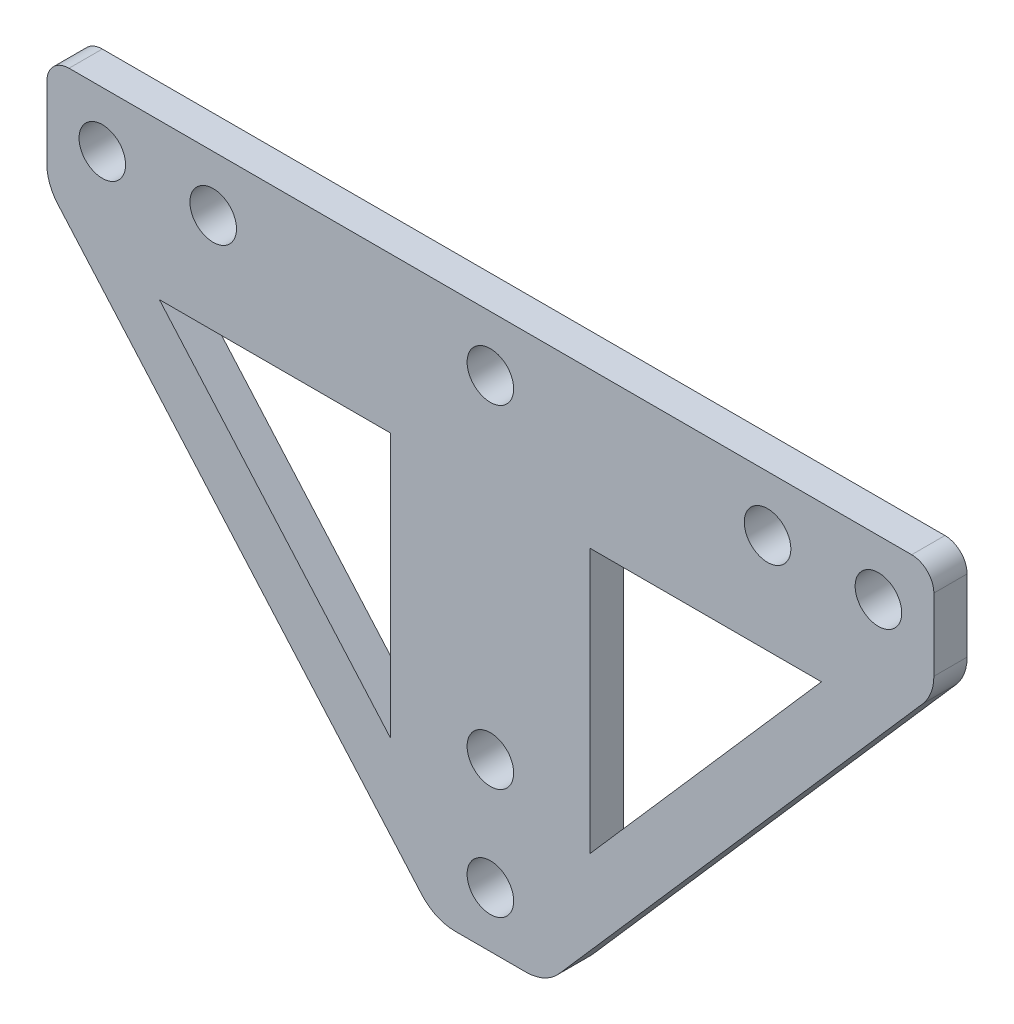
SolidWorks part; units mm, degrees
ref_plane "前视基准面" through (0, 0, 0) normal (0, 0, 1) x (1, 0, 0)
ref_plane "上视基准面" through (0, 0, 0) normal (0, 1, 0) x (1, 0, 0)
ref_plane "右视基准面" through (0, 0, 0) normal (1, 0, 0) x (0, 0, -1)
other "Configuration Table"
sketch "草图1" plane through (0, 0, 0) normal (0, 0, 1) x (1, 0, 0)
  line L0 (0, 0) -> (80, 0)
  line L1 (80, 0) -> (80, -10)
  line L2 (80, -10) -> (45, -50)
  line L3 (45, -50) -> (35, -50)
  line L4 (35, -50) -> (0, -10)
  line L5 (0, -10) -> (0, 0)
  line L6 (40, 0) -> (40, -50) construction
  point P9 (0, -10)
  point P10 (0, 0)
  dimension "D1" = 10
  dimension "D2" = 10
  dimension "D3" = 80
  dimension "D4" = 40
extrude "凸台-拉伸1" add sketch "草图1" along normal blind 3
sketch "草图2" plane through (0, 0, 3) normal (0, 0, 1) x (1, 0, 0)
  line L0 (0, -5) -> (80, -5) construction
  line L1 (0, 0) -> (0, -10) construction
  line L2 (80, -10) -> (80, 0) construction
  line L3 (40, -50) -> (40, 0) construction
  line L4 (35, -50) -> (45, -50) construction
  line L5 (80, 0) -> (0, 0) construction
  circle A0 centre (5, -5) radius 2.1
  circle A1 centre (15, -5) radius 2.1
  circle A2 centre (65, -5) radius 2.1
  circle A3 centre (75, -5) radius 2.1
  circle A4 centre (40, -45) radius 2.1
  circle A5 centre (40, -35) radius 2.1
  circle A6 centre (40, -5) radius 2.1
  dimension "D1" = 4.2
  dimension "D2" = 5
  dimension "D4" = 4.2
  dimension "D6" = 10
  dimension "D7" = 4.2
  dimension "D3" = 10
  dimension "D5" = 5
extrude "切除-拉伸1" cut sketch "草图2" against normal through all
sketch "草图3" plane through (0, 0, 3) normal (0, 0, 1) x (1, 0, 0)
  line L0 (10.1438, -14) -> (31, -14)
  line L1 (31, -14) -> (31, -37.8356)
  line L2 (31, -37.8356) -> (10.1438, -14)
  line L3 (40, 0) -> (40, -50) construction
  line L4 (80, 0) -> (0, 0) construction
  line L5 (35, -50) -> (45, -50) construction
  line L7 (0, -10) -> (35, -50) construction
  line L8 (49, -37.8356) -> (69.8562, -14)
  line L9 (49, -14) -> (49, -37.8356)
  line L10 (69.8562, -14) -> (49, -14)
  point P10 (33, -39.6322)
  dimension "D1" = 14
  dimension "D2" = 9
  dimension "D3" = 5
extrude "切除-拉伸2" cut sketch "草图3" against normal through all
fillet "圆角1" radius 2 2 edges at (0, 0, 1.5) (80, 0, 1.5)
fillet "圆角2" radius 4 4 edges at (80, -10, 1.5) (0, -10, 1.5) (45, -50, 1.5) (35, -50, 1.5)
